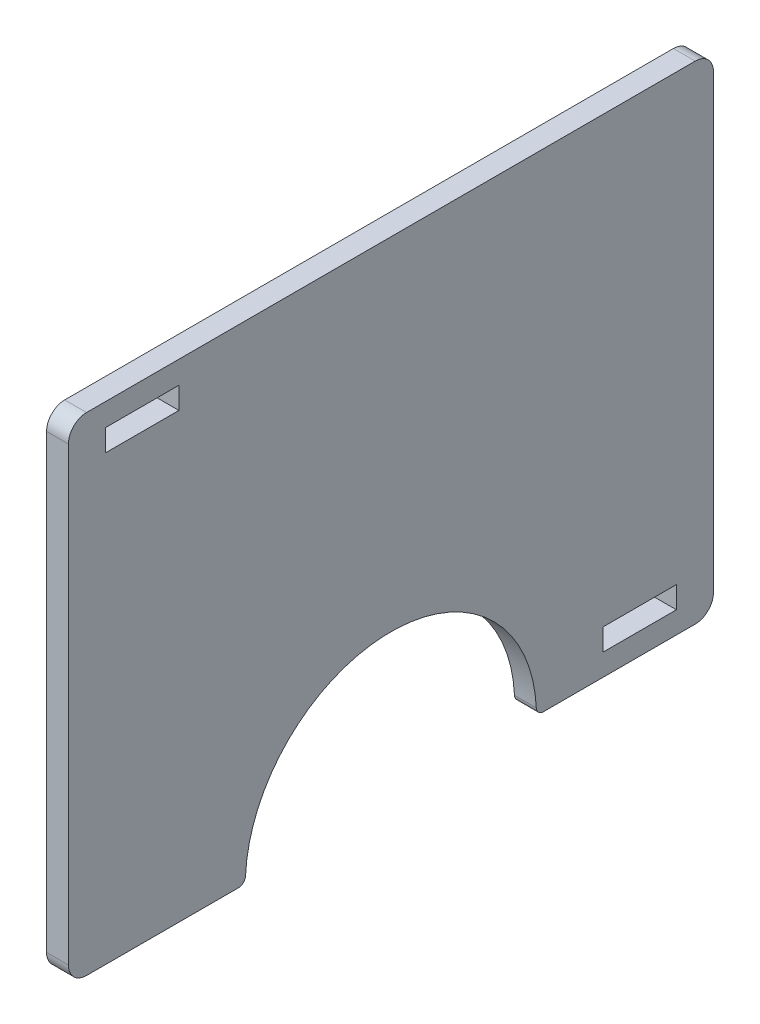
SolidWorks part; units mm, degrees
ref_plane "Alzado" through (0, 0, 0) normal (0, 0, 1) x (1, 0, 0)
ref_plane "Planta" through (0, 0, 0) normal (0, 1, 0) x (1, 0, 0)
ref_plane "Vista lateral" through (0, 0, 0) normal (1, 0, 0) x (0, 0, -1)
sketch "Croquis1" plane through (0, 0, 0) normal (1, 0, 0) x (0, 0, -1)
  line L1 (-41.82, 33.5) -> (41.82, 33.5)
  line L2 (-44.32, 31) -> (-44.32, -31)
  line L3 (-41.82, -33.5) -> (41.82, -33.5)
  line L4 (44.32, 31) -> (44.32, -31)
  line L5 (-44.32, 33.5) -> (44.32, -33.5) construction
  line L6 (-44.32, -33.5) -> (44.32, 33.5) construction
  arc A0 (-44.32, -31) -> (-41.82, -33.5) centre (-41.82, -31) ccw
  arc A1 (41.82, -33.5) -> (44.32, -31) centre (41.82, -31) ccw
  arc A2 (41.82, 33.5) -> (44.32, 31) centre (41.82, 31) cw
  arc A3 (-41.82, 33.5) -> (-44.32, 31) centre (-41.82, 31) ccw
  point P0 (0, 0)
  point P18 (-29.32, -33.5)
  dimension "D3" = 2.5
  dimension "D1" = 88.64
  dimension "D2" = 67
extrude "Saliente-Extruir1" add sketch "Croquis1" along normal blind 3
sketch "Croquis2" plane through (3, 0, 0) normal (1, 0, 0) x (0, 0, -1)
  line L0 (-41.82, -33.5) -> (41.82, -33.5) construction
  line L1 (44.32, -31) -> (44.32, 31) construction
  line L2 (-44.32, 31) -> (-44.32, -31) construction
  line L15 (0, 5.1674) -> (0, -3.1373) construction
  line L17 (-3.7832, 1.015) -> (6.0901, 1.015) construction
  line L18 (39.23, -27.5) -> (29.13, -27.5)
  line L19 (29.13, -30.5) -> (29.13, -27.5)
  line L20 (39.23, -30.5) -> (29.13, -30.5)
  line L21 (39.23, -30.5) -> (39.23, -27.5)
  line L22 (-39.23, 30.4) -> (-29.13, 30.4)
  line L23 (-29.13, 27.4) -> (-29.13, 30.4)
  line L24 (-39.23, 27.4) -> (-29.13, 27.4)
  line L25 (-39.23, 27.4) -> (-39.23, 30.4)
  circle A0 centre (0, -33.5) radius 20
  dimension "D1" = 40
  dimension "D2" = 3
  dimension "D3" = 3
  dimension "D4" = 5.09
  dimension "D5" = 5.09
extrude "Cortar-Extruir1" cut sketch "Croquis2" against normal mid plane 6
fillet "Redondeo1" radius 1 2 edges at (1.5, -33.5, -20) (1.5, -33.5, 20)
